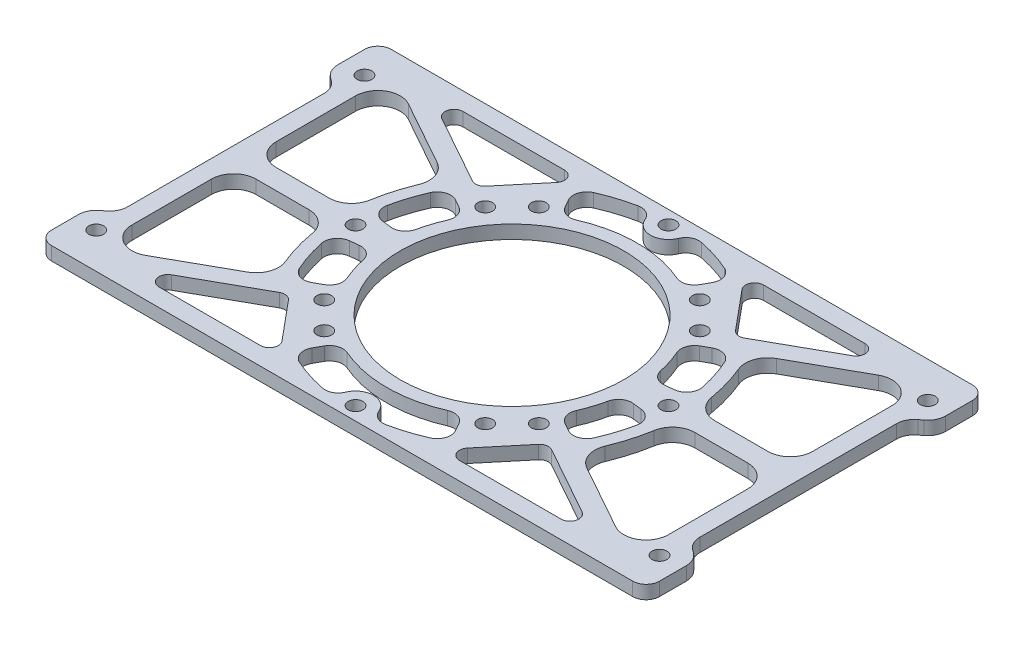
SolidWorks part; units mm, degrees
material "A-玻璃纤维"
ref_plane "前视基准面" through (0, 0, 0) normal (0, 0, 1) x (1, 0, 0)
ref_plane "上视基准面" through (0, 0, 0) normal (0, 1, 0) x (1, 0, 0)
ref_plane "右视基准面" through (0, 0, 0) normal (1, 0, 0) x (0, 0, -1)
other "Configuration Table"
sketch "草图1" plane through (0, 0, 0) normal (0, 1, 0) x (1, 0, 0)
  line L0 (-63, 38) -> (-63, -38) construction
  line L1 (-68, -38) -> (68, -38)
  line L2 (-68, -38) -> (-68, 38)
  line L3 (-68, 38) -> (68, 38)
  line L4 (68, -38) -> (68, 38)
  line L5 (-68, -38) -> (68, 38) construction
  line L6 (-68, 38) -> (68, -38) construction
  line L7 (0, 0) -> (0, 38) construction
  line L8 (-60, 38) -> (-60, -38) construction
  line L9 (-18, -24) -> (18, -24) construction
  line L10 (-18, -24) -> (-18, 24) construction
  line L11 (-18, 24) -> (18, 24) construction
  line L12 (18, -24) -> (18, 24) construction
  line L13 (-18, -24) -> (18, 24) construction
  line L14 (-18, 24) -> (18, -24) construction
  line L15 (-24, -18) -> (24, -18) construction
  line L16 (-24, -18) -> (-24, 18) construction
  line L17 (-24, 18) -> (24, 18) construction
  line L18 (24, -18) -> (24, 18) construction
  line L19 (-24, -18) -> (24, 18) construction
  line L20 (-24, 18) -> (24, -18) construction
  line L27 (0, 0) -> (-68, 0) construction
  line L53 (-33.8266, 18.9031) -> (-60, 33.5294)
  line L54 (-60, 33.5294) -> (-60, -33.5294) construction
  line L55 (-60, -33.5294) -> (-33.8266, -18.9031)
  line L59 (-60, 2.25) -> (-38.6846, 2.25)
  line L60 (-60, -2.25) -> (-38.6846, -2.25)
  line L61 (-60, 2.25) -> (-60, 33.5294)
  line L62 (-60, -2.25) -> (-60, -33.5294)
  line L63 (60, -2.25) -> (60, -33.5294)
  line L64 (60, -2.25) -> (38.6846, -2.25)
  line L65 (60, -33.5294) -> (33.8266, -18.9031)
  line L66 (60, 2.25) -> (60, 33.5294)
  line L67 (33.8266, 18.9031) -> (60, 33.5294)
  line L68 (60, 2.25) -> (38.6846, 2.25)
  circle A0 centre (0, 0) radius 25
  circle A1 centre (-63, 30) radius 1.65
  circle A2 centre (-63, -30) radius 1.65
  circle A3 centre (-18, 24) radius 1.65
  circle A4 centre (18, 24) radius 1.65
  circle A5 centre (-24, 18) radius 1.65
  circle A6 centre (24, 18) radius 1.65
  circle A7 centre (24, -18) radius 1.65
  circle A8 centre (18, -24) radius 1.65
  circle A9 centre (-18, -24) radius 1.65
  circle A10 centre (-24, -18) radius 1.65
  circle A11 centre (0, 0) radius 35 construction
  circle A12 centre (63, -30) radius 1.65
  circle A13 centre (63, 30) radius 1.65
  circle A15 centre (0, 35) radius 1.65
  circle A24 centre (35, 0) radius 1.65
  circle A25 centre (0, -35) radius 1.65
  circle A26 centre (-35, 0) radius 1.65
  circle A28 centre (0, 0) radius 38.75 construction
  arc A29 (-33.8266, 18.9031) -> (-33.8266, -18.9031) centre (0, 0) ccw construction
  arc A31 (-33.8266, 18.9031) -> (-38.6846, 2.25) centre (0, 0) ccw
  arc A32 (-38.6846, -2.25) -> (-33.8266, -18.9031) centre (0, 0) ccw
  arc A33 (38.6846, -2.25) -> (33.8266, -18.9031) centre (0, 0) cw
  arc A34 (33.8266, 18.9031) -> (38.6846, 2.25) centre (0, 0) cw
  point P0 (0, 0)
  point P61 (0, 0)
  dimension "D3" = 50
  dimension "D5" = 3.3
  dimension "D6" = 8
  dimension "D7" = 8
  dimension "D12" = 3.3
  dimension "D13" = 70
  dimension "D15" = 4
  dimension "D16" = 77.5
  dimension "D2" = 60
  dimension "D4" = 5
  dimension "D8" = 36
  dimension "D9" = 48
  dimension "D10" = 36
  dimension "D11" = 48
  dimension "D14" = 8
  dimension "D17" = 4.5
  dimension "D18" = 63
extrude "凸台-拉伸1" add sketch "草图1" along normal blind 3
fillet "圆角2" radius 3 4 edges at (68, 1.5, 38) (-68, 1.5, 38) (68, 1.5, -38) (-68, 1.5, -38)
fillet "圆角3" radius 5 16 edges at (60, 1.5, -2.25) (60, 1.5, -33.5294) (33.8266, 1.5, -18.9031) (38.6846, 1.5, -2.25) (-60, 1.5, 33.5294) (-33.8266, 1.5, 18.9031) (-38.6846, 1.5, 2.25) (-60, 1.5, 2.25) (-33.8266, 1.5, -18.9031) (-60, 1.5, -2.25) (-38.6846, 1.5, -2.25) (38.6846, 1.5, 2.25) (33.8266, 1.5, 18.9031) (60, 1.5, 33.5294) (60, 1.5, 2.25) (-60, 1.5, -33.5294)
sketch "草图2" plane through (0, 3, 0) normal (0, 1, 0) x (1, 0, 0)
  line L0 (-52.6424, 34) -> (-29, 20.7881)
  line L1 (-29, 20.7881) -> (-18, 34)
  line L2 (-18, 34) -> (-52.6424, 34)
  line L3 (0, -1000) -> (0, 49000) construction
  line L4 (-1000, 0) -> (49000, 0) construction
  line L5 (-37.941, 21.2023) -> (-52.5609, 29.3723) construction
  line L6 (65, 38) -> (-65, 38) construction
  line L7 (-18, -34) -> (-52.6424, -34)
  line L8 (-29, -20.7881) -> (-18, -34)
  line L9 (-52.6424, -34) -> (-29, -20.7881)
  line L10 (52.6424, -34) -> (29, -20.7881)
  line L11 (29, -20.7881) -> (18, -34)
  line L12 (18, -34) -> (52.6424, -34)
  line L13 (18, 34) -> (52.6424, 34)
  line L14 (29, 20.7881) -> (18, 34)
  line L15 (52.6424, 34) -> (29, 20.7881)
  dimension "D1" = 4
  dimension "D2" = 4
  dimension "D3" = 29
  dimension "D4" = 18
extrude "切除-拉伸1" cut sketch "草图2" against normal blind 10
fillet "圆角4" radius 2 12 edges at (-18, 1.5, -34) (-52.6424, 1.5, -34) (-18, 1.5, 34) (-52.6424, 1.5, 34) (-29, 1.5, 20.7881) (18, 1.5, 34) (29, 1.5, 20.7881) (52.6424, 1.5, 34) (18, 1.5, -34) (52.6424, 1.5, -34) (29, 1.5, -20.7881) (-29, 1.5, -20.7881)
sketch "草图3" plane through (0, 3, 0) normal (0, 1, 0) x (1, 0, 0)
  line L0 (0, 0) -> (-35.7641, 4.1143) construction
  line L1 (0, 0) -> (-31.4229, 17.5671) construction
  line L2 (-35.7641, 4.1143) -> (-27.8165, 3.2)
  line L3 (-24.44, 13.6633) -> (-31.4229, 17.5671)
  line L4 (-1000, 0) -> (49000, 0) construction
  line L5 (0, -1000.6563) -> (0, 48999.3437) construction
  line L6 (-35.7641, -4.1143) -> (-27.8165, -3.2)
  line L7 (-24.44, -13.6633) -> (-31.4229, -17.5671)
  line L8 (35.7641, -4.1143) -> (27.8165, -3.2)
  line L9 (24.44, -13.6633) -> (31.4229, -17.5671)
  line L10 (35.7641, 4.1143) -> (27.8165, 3.2)
  line L11 (24.44, 13.6633) -> (31.4229, 17.5671)
  line L12 (-68, 27) -> (-64, 24)
  line L13 (-68, 35) -> (-68, -35) construction
  line L14 (-64, 24) -> (-64, -24)
  line L15 (-64, -24) -> (-68, -27)
  line L16 (-68, -27) -> (-68, 27)
  line L17 (64, -24) -> (68, -27)
  line L18 (64, 24) -> (64, -24)
  line L19 (68, 27) -> (64, 24)
  line L20 (68, -27) -> (68, 27)
  line L21 (-13.6633, 24.44) -> (-17.5671, 31.4229)
  line L22 (13.6633, 24.44) -> (17.5671, 31.4229)
  line L23 (-13.6633, -24.44) -> (-17.5671, -31.4229)
  line L24 (13.6633, -24.44) -> (17.5671, -31.4229)
  arc A0 (-35.7641, 4.1143) -> (-31.4229, 17.5671) centre (0, 0) cw
  arc A1 (-27.8165, 3.2) -> (-24.44, 13.6633) centre (0, 0) cw
  circle A2 centre (-35, 0) radius 1.65 construction
  circle A3 centre (-24, 18) radius 1.65 construction
  arc A4 (-27.8165, -3.2) -> (-24.44, -13.6633) centre (0, 0) ccw
  arc A5 (-35.7641, -4.1143) -> (-31.4229, -17.5671) centre (0, 0) ccw
  arc A6 (35.7641, -4.1143) -> (31.4229, -17.5671) centre (0, 0) cw
  arc A7 (27.8165, -3.2) -> (24.44, -13.6633) centre (0, 0) cw
  arc A8 (27.8165, 3.2) -> (24.44, 13.6633) centre (0, 0) ccw
  arc A9 (35.7641, 4.1143) -> (31.4229, 17.5671) centre (0, 0) ccw
  arc A10 (-17.5671, 31.4229) -> (-3.9221, 35.7857) centre (0, 0) cw
  arc A11 (-13.6633, 24.44) -> (13.6633, 24.44) centre (0, 0) cw
  circle A12 centre (-18, 24) radius 1.65 construction
  circle A13 centre (18, 24) radius 1.65 construction
  circle A14 centre (0, 0) radius 25 construction
  arc A15 (-3.9221, 35.7857) -> (3.9221, 35.7857) centre (0, 35) ccw
  arc A16 (3.9221, 35.7857) -> (17.5671, 31.4229) centre (0, 0) cw
  arc A17 (-13.6633, -24.44) -> (13.6633, -24.44) centre (0, 0) ccw
  arc A18 (3.9221, -35.7857) -> (17.5671, -31.4229) centre (0, 0) ccw
  arc A19 (-3.9221, -35.7857) -> (3.9221, -35.7857) centre (0, -35) cw
  arc A20 (-17.5671, -31.4229) -> (-3.9221, -35.7857) centre (0, 0) ccw
  dimension "D2" = 4
  dimension "D3" = 28
  dimension "D4" = 36
  dimension "D12" = 3
  dimension "D13" = 36
  dimension "D14" = 8
  dimension "D1" = 4
  dimension "D5" = 27
  dimension "D6" = 27
  dimension "D7" = 24
  dimension "D8" = 24
  dimension "D9" = 4
  dimension "D10" = 4
  dimension "D11" = 4
extrude "切除-拉伸2" cut sketch "草图3" against normal through all
fillet "圆角5" radius 3 28 edges at (-24.44, 1.5, -13.6633) (-27.8165, 1.5, -3.2) (-35.7641, 1.5, -4.1143) (13.6633, 1.5, 24.44) (17.5671, 1.5, 31.4229) (3.9221, 1.5, 35.7857) (-3.9221, 1.5, 35.7857) (-17.5671, 1.5, 31.4229) (-13.6633, 1.5, 24.44) (17.5671, 1.5, -31.4229) (13.6633, 1.5, -24.44) (-13.6633, 1.5, -24.44) (-17.5671, 1.5, -31.4229) (-3.9221, 1.5, -35.7857) (3.9221, 1.5, -35.7857) (24.44, 1.5, -13.6633) (31.4229, 1.5, -17.5671) (35.7641, 1.5, -4.1143) (27.8165, 1.5, -3.2) (-24.44, 1.5, 13.6633) (-31.4229, 1.5, 17.5671) (-35.7641, 1.5, 4.1143) (-27.8165, 1.5, 3.2) (31.4229, 1.5, 17.5671) (24.44, 1.5, 13.6633) (27.8165, 1.5, 3.2) (35.7641, 1.5, 4.1143) (-31.4229, 1.5, -17.5671)
fillet "圆角6" radius 4 8 edges at (-68, 1.5, 27) (68, 1.5, 27) (64, 1.5, 24) (64, 1.5, -24) (68, 1.5, -27) (-64, 1.5, -24) (-64, 1.5, 24) (-68, 1.5, -27)
